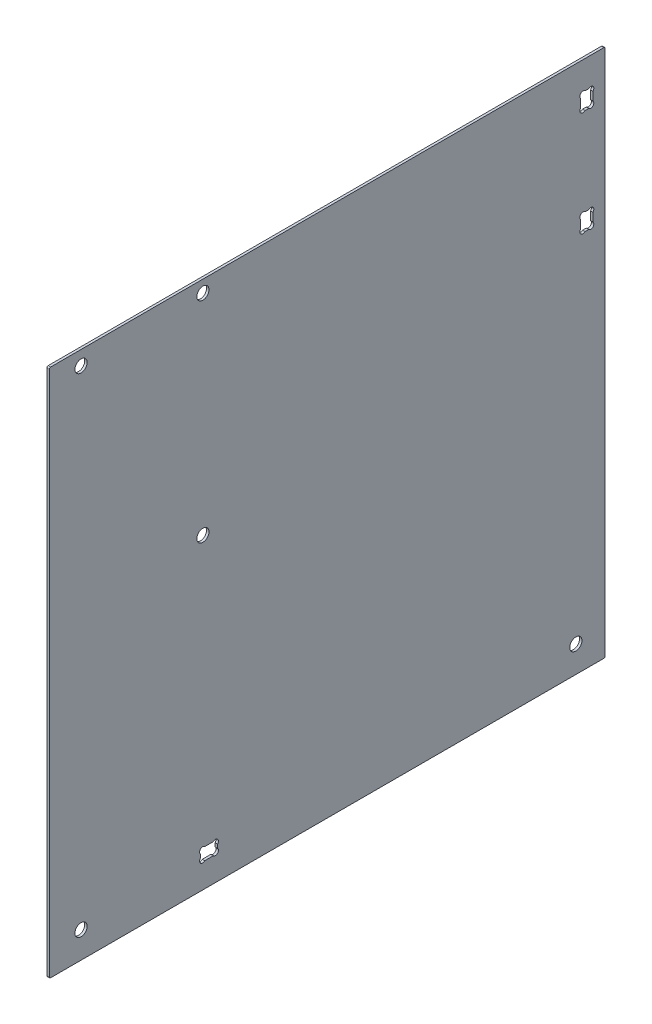
SolidWorks part; units mm, degrees
ref_plane "Front Plane" through (0, 0, 0) normal (0, 0, 1) x (1, 0, 0)
ref_plane "Top Plane" through (0, 0, 0) normal (0, 1, 0) x (1, 0, 0)
ref_plane "Right Plane" through (0, 0, 0) normal (1, 0, 0) x (0, 0, -1)
sketch "Sketch1" plane through (0, 0, 0) normal (1, 0, 0) x (0, 0, -1)
  line L0 (-228, 0) -> (-228, 217)
  line L1 (-228, 0) -> (0, 0)
  line L3 (-228, 217) -> (0, 217)
  line L4 (0, 0) -> (0, 217)
  line L11 (-10, 205.5) -> (-5, 205.5)
  line L12 (-10, 205.5) -> (-10, 198.5)
  line L13 (-10, 198.5) -> (-5, 198.5)
  line L14 (-5, 205.5) -> (-5, 198.5)
  line L15 (-5, 162.5) -> (-10, 162.5)
  line L16 (-5, 162.5) -> (-5, 155.5)
  line L17 (-5, 155.5) -> (-10, 155.5)
  line L18 (-10, 162.5) -> (-10, 155.5)
  line L22 (-159, 15) -> (-166, 15)
  line L23 (-159, 15) -> (-159, 10)
  line L24 (-159, 10) -> (-166, 10)
  line L25 (-166, 15) -> (-166, 10)
  circle A0 centre (-215, 10.85) radius 1.65 construction
  circle A1 centre (-215, 10.85) radius 2.5
  circle A2 centre (-215, 211.15) radius 2.5
  circle A3 centre (-165, 212) radius 2.5
  circle A4 centre (-215, 211.15) radius 1.65 construction
  circle A5 centre (-165, 126) radius 2.5
  circle A6 centre (-12, 10.85) radius 1.65 construction
  circle A7 centre (-12, 10.85) radius 2.5
  dimension "D5" = 10.85
  dimension "D21" = 5
  dimension "D22" = 3.3
  dimension "D23" = 5
  dimension "D1" = 217
  dimension "D3" = 5
  dimension "D4" = 49
  dimension "D6" = 203
  dimension "D7" = 200.3
  dimension "D8" = 165
  dimension "D9" = 5
  dimension "D10" = 7
  dimension "D11" = 215
  dimension "D12" = 86
  dimension "D13" = 228
  dimension "D16" = 11.5
  dimension "D17" = 54.5
  dimension "D18" = 5
  dimension "D19" = 7
  dimension "D25" = 5
  dimension "D26" = 15
extrude "Boss-Extrude1" add sketch "Sketch1" along normal blind 1
sketch "Sketch3" plane through (0, 0, 0) normal (-1, 0, 0) x (0, 0, 1)
  line L0 (7.5, 205.5) -> (7.5, 203.1766) construction
  line L1 (166, 12.5) -> (162.5, 12.5) construction
  line L2 (5, 205.5) -> (10, 205.5) construction
  line L3 (5, 202) -> (10, 202) construction
  line L4 (5, 198.5) -> (5, 205.5) construction
  line L5 (5.8839, 205.5) -> (5.8839, 204.6161) construction
  line L6 (5.8839, 204.6161) -> (5, 204.6161) construction
  line L7 (166, 15) -> (166, 10) construction
  line L8 (162.5, 12.5) -> (162.5, 15) construction
  line L9 (159, 15) -> (166, 15) construction
  line L10 (4.1161, 180.5) -> (24.4088, 180.5) construction
  line L11 (5, 162.5) -> (10, 162.5) construction
  line L12 (10, 198.5) -> (5, 198.5) construction
  line L13 (10, 205.5) -> (10, 198.5) construction
  line L14 (165.1161, 15) -> (165.1161, 14.1161) construction
  line L16 (159, 15) -> (166, 15) construction
  line L17 (165.1161, 14.1161) -> (166, 14.1161) construction
  line L18 (166, 15) -> (166, 10) construction
  circle A0 centre (5.8839, 204.6161) radius 1.25
  circle A1 centre (9.1161, 204.6161) radius 1.25
  circle A2 centre (5.8839, 199.3839) radius 1.25
  circle A3 centre (9.1161, 199.3839) radius 1.25
  circle A4 centre (9.1161, 161.6161) radius 1.25
  circle A5 centre (5.8839, 161.6161) radius 1.25
  circle A6 centre (9.1161, 156.3839) radius 1.25
  circle A7 centre (5.8839, 156.3839) radius 1.25
  circle A8 centre (165.1161, 14.1161) radius 1.25
  circle A9 centre (165.1161, 10.8839) radius 1.25
  circle A10 centre (159.8839, 10.8839) radius 1.25
  circle A11 centre (159.8839, 14.1161) radius 1.25
  dimension "D1" = 2.5
  dimension "D2" = 2.5
extrude "Cut-Extrude3" cut sketch "Sketch3" against normal through all
fillet "Fillet1" radius 0.5 4 edges at (0.5, 217, 228) (0.5, 0, 228) (0.5, 0, 0) (0.5, 217, 0)
